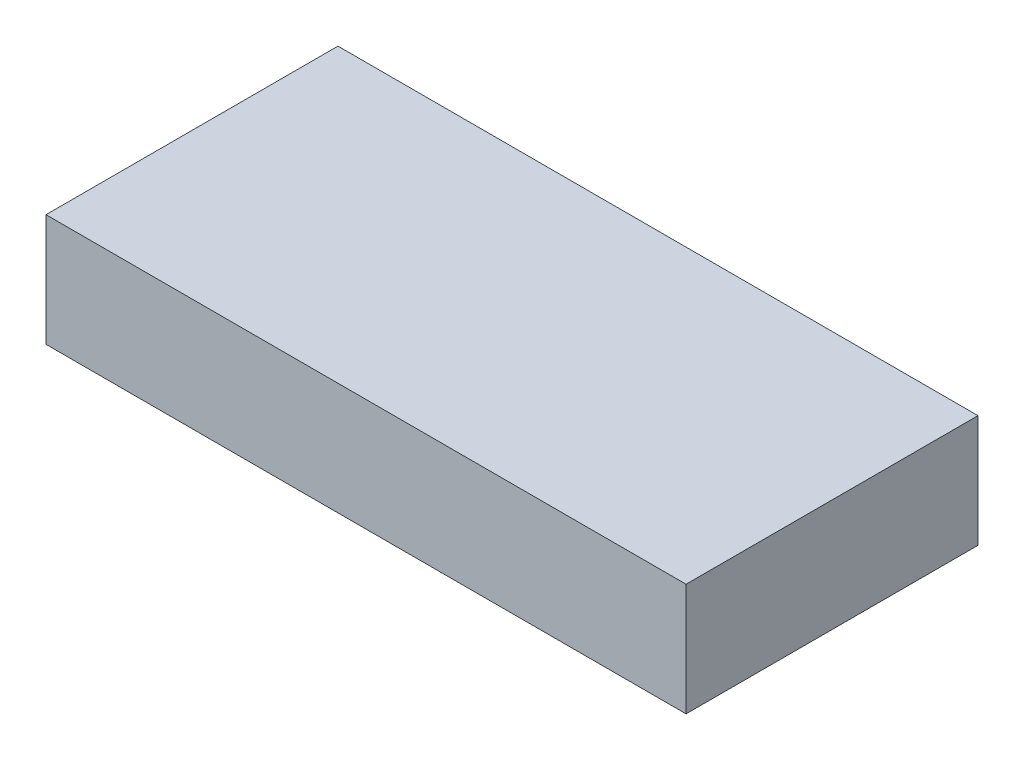
SolidWorks part; units mm, degrees
material "PA Type 6"
ref_plane "Front Plane" through (0, 0, 0) normal (0, 0, 1) x (1, 0, 0)
ref_plane "Top Plane" through (0, 0, 0) normal (0, 1, 0) x (1, 0, 0)
ref_plane "Right Plane" through (0, 0, 0) normal (1, 0, 0) x (0, 0, -1)
sketch "Sketch1" plane through (0, 0, 0) normal (0, 1, 0) x (1, 0, 0)
  line L1 (-14.25, -6.5) -> (14.25, -6.5)
  line L2 (-14.25, -6.5) -> (-14.25, 6.5)
  line L3 (-14.25, 6.5) -> (14.25, 6.5)
  line L4 (14.25, -6.5) -> (14.25, 6.5)
  line L5 (-14.25, -6.5) -> (14.25, 6.5) construction
  line L6 (-14.25, 6.5) -> (14.25, -6.5) construction
  point P0 (0, 0)
  dimension "D1" = 13
  dimension "D2" = 28.5
extrude "Boss-Extrude1" add sketch "Sketch1" along normal mid plane 5
